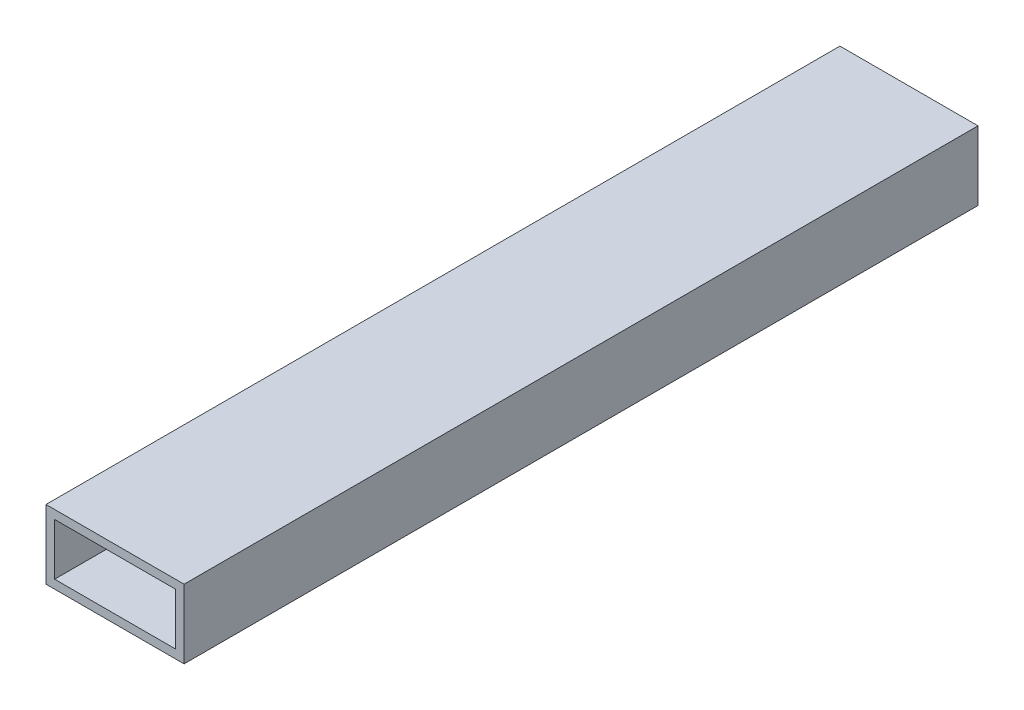
SolidWorks part; units mm, degrees
ref_plane "Front Plane" through (0, 0, 0) normal (0, 0, 1) x (1, 0, 0)
ref_plane "Top Plane" through (0, 0, 0) normal (0, 1, 0) x (1, 0, 0)
ref_plane "Right Plane" through (0, 0, 0) normal (1, 0, 0) x (0, 0, -1)
sketch "Sketch1" plane through (0, 0, 0) normal (0, 0, 1) x (1, 0, 0)
  line L0 (3.175, 22.225) -> (47.625, 22.225)
  line L1 (0, 0) -> (50.8, 0)
  line L2 (0, 0) -> (0, 25.4)
  line L3 (0, 25.4) -> (50.8, 25.4)
  line L4 (50.8, 0) -> (50.8, 25.4)
  line L5 (47.625, 3.175) -> (47.625, 22.225)
  line L6 (3.175, 3.175) -> (47.625, 3.175)
  line L7 (3.175, 3.175) -> (3.175, 22.225)
  dimension "D1" = 50.8
  dimension "D2" = 25.4
  dimension "D3" = 3.175
extrude "Boss-Extrude1" add sketch "Sketch1" along normal blind 292.1
